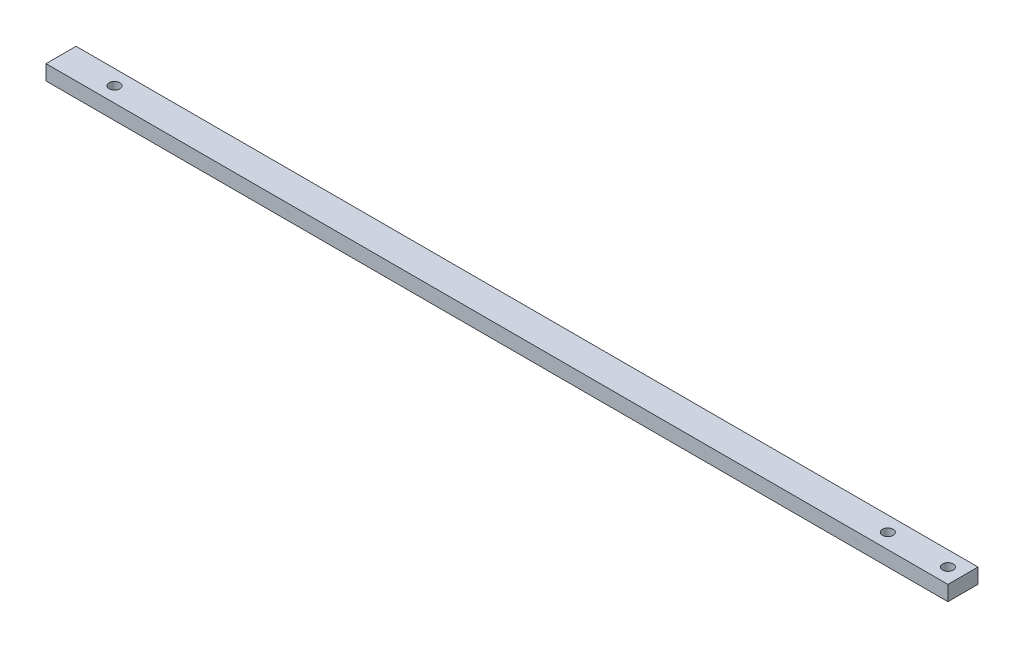
SolidWorks part; units mm, degrees
ref_plane "Front Plane" through (0, 0, 0) normal (0, 0, 1) x (1, 0, 0)
ref_plane "Top Plane" through (0, 0, 0) normal (0, 1, 0) x (1, 0, 0)
ref_plane "Right Plane" through (0, 0, 0) normal (1, 0, 0) x (0, 0, -1)
sketch "Sketch1" plane through (0, 0, 0) normal (0, 1, 0) x (1, 0, 0)
  line L0 (0, 6.35) -> (22.5679, 6.35)
  line L1 (0, 0) -> (381, 0)
  line L2 (0, 0) -> (0, 12.7)
  line L3 (0, 12.7) -> (381, 12.7)
  line L4 (381, 0) -> (381, 12.7)
  circle A0 centre (22.5679, 6.35) radius 2.2479
  circle A1 centre (349.25, 6.35) radius 2.2479
  circle A2 centre (374.65, 6.35) radius 2.2479
  dimension "D1" = 381
  dimension "D2" = 12.7
  dimension "D3" = 22.5679
extrude "Boss-Extrude2" add sketch "Sketch1" along normal blind 6.35
